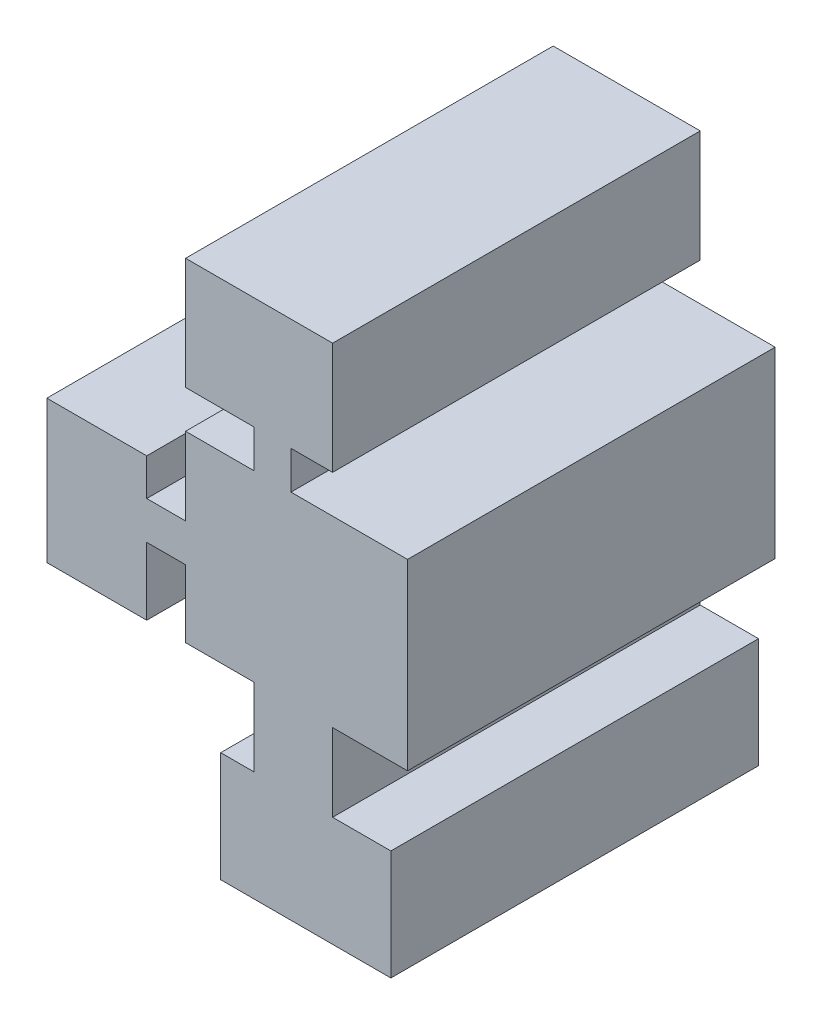
SolidWorks part; units mm, degrees
ref_plane "Front Plane" through (0, 0, 0) normal (0, 0, 1) x (1, 0, 0)
ref_plane "Top Plane" through (0, 0, 0) normal (0, 1, 0) x (1, 0, 0)
ref_plane "Right Plane" through (0, 0, 0) normal (1, 0, 0) x (0, 0, -1)
sketch "Sketch1" plane through (0, 0, 0) normal (0, 0, 1) x (1, 0, 0)
  line L0 (127, 271.5) -> (635, 271.5) construction
  line L1 (543.0906, 88.9759) -> (543.0906, 83.9951)
  line L2 (543.0906, 83.9951) -> (541.053, 83.9951)
  line L3 (541.053, 83.9951) -> (541.053, 81.8821)
  line L4 (541.053, 81.8821) -> (542.6378, 81.8821)
  line L5 (542.6378, 81.8821) -> (542.6378, 78.8886)
  line L6 (542.6378, 78.8886) -> (538.0092, 78.8886)
  line L7 (538.0092, 78.8886) -> (538.0092, 81.8821)
  line L8 (538.0092, 81.8821) -> (538.9148, 81.8821)
  line L9 (538.9148, 81.8821) -> (538.9148, 83.9951)
  line L10 (538.9148, 83.9951) -> (537.0533, 83.9951)
  line L11 (537.0533, 83.9951) -> (537.0533, 85.8315)
  line L12 (537.0533, 85.8315) -> (535.9968, 85.8315)
  line L13 (535.9968, 85.8315) -> (535.9968, 83.9951)
  line L14 (535.9968, 83.9951) -> (533.28, 83.9951)
  line L15 (533.28, 83.9951) -> (533.28, 87.8691)
  line L16 (533.28, 87.8691) -> (535.9968, 87.8691)
  line L17 (535.9968, 87.8691) -> (535.9968, 86.8628)
  line L18 (535.9968, 86.8628) -> (537.0533, 86.8628)
  line L19 (537.0533, 86.8628) -> (537.0533, 88.9759)
  line L20 (537.0533, 88.9759) -> (538.9148, 88.9759)
  line L21 (538.9148, 88.9759) -> (538.9148, 90.0073)
  line L22 (538.9148, 90.0073) -> (537.0533, 90.0073)
  line L23 (537.0533, 90.0073) -> (537.0533, 93.0511)
  line L24 (537.0533, 93.0511) -> (541.053, 93.0511)
  line L25 (541.053, 93.0511) -> (541.053, 90.0073)
  line L26 (541.053, 90.0073) -> (539.921, 90.0073)
  line L27 (539.921, 90.0073) -> (539.921, 88.9759)
  line L28 (539.921, 88.9759) -> (543.0906, 88.9759)
extrude "Boss-Extrude1" add sketch "Sketch1" along normal blind 10
